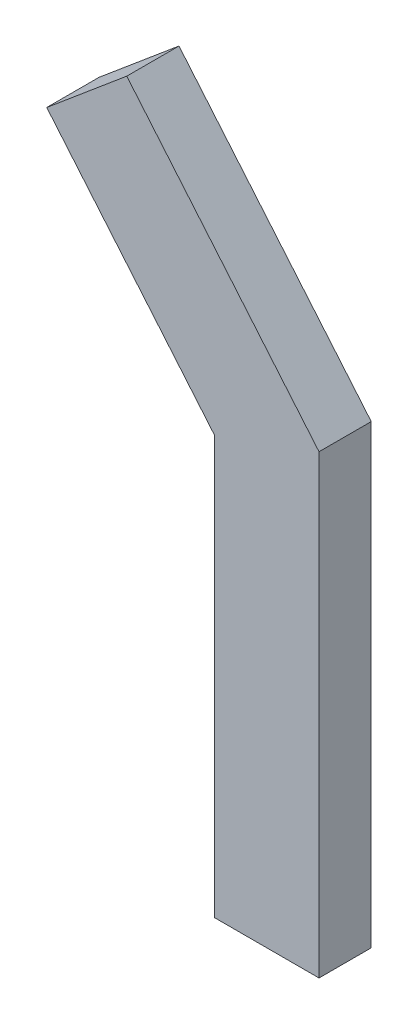
SolidWorks part; units mm, degrees
ref_plane "前基準面" through (0, 0, 0) normal (0, 0, 1) x (1, 0, 0)
ref_plane "上基準面" through (0, 0, 0) normal (0, 1, 0) x (1, 0, 0)
ref_plane "右基準面" through (0, 0, 0) normal (1, 0, 0) x (0, 0, -1)
sketch "草圖1" plane through (0, 0, 0) normal (0, 0, 1) x (1, 0, 0)
  line L0 (0, 0) -> (0, 0.8)
  line L1 (0, 0.8) -> (-0.3214, 1.183)
  line L2 (0.2, 0) -> (0.2, 0.8728)
  line L3 (0.2, 0.8728) -> (-0.1682, 1.3116)
  line L4 (-0.3214, 1.183) -> (-0.1682, 1.3116)
  line L5 (0, 0) -> (0.2, 0)
  dimension "D1" = 0.8
  dimension "D2" = 0.5
  dimension "D3" = 140
  dimension "D4" = 0.2
extrude "填料-伸長1" add sketch "草圖1" along normal blind 0.1
sketch "草圖3" plane through (0, 0, 0) normal (0, -1, 0) x (1, 0, 0)
  line L0 (0.2, 0.05) -> (5, 0.05)
  line L1 (0.2, 0.1) -> (0.2, 0) construction
  circle A0 centre (5, 0.05) radius 1.6909
  dimension "D1" = 4.8
